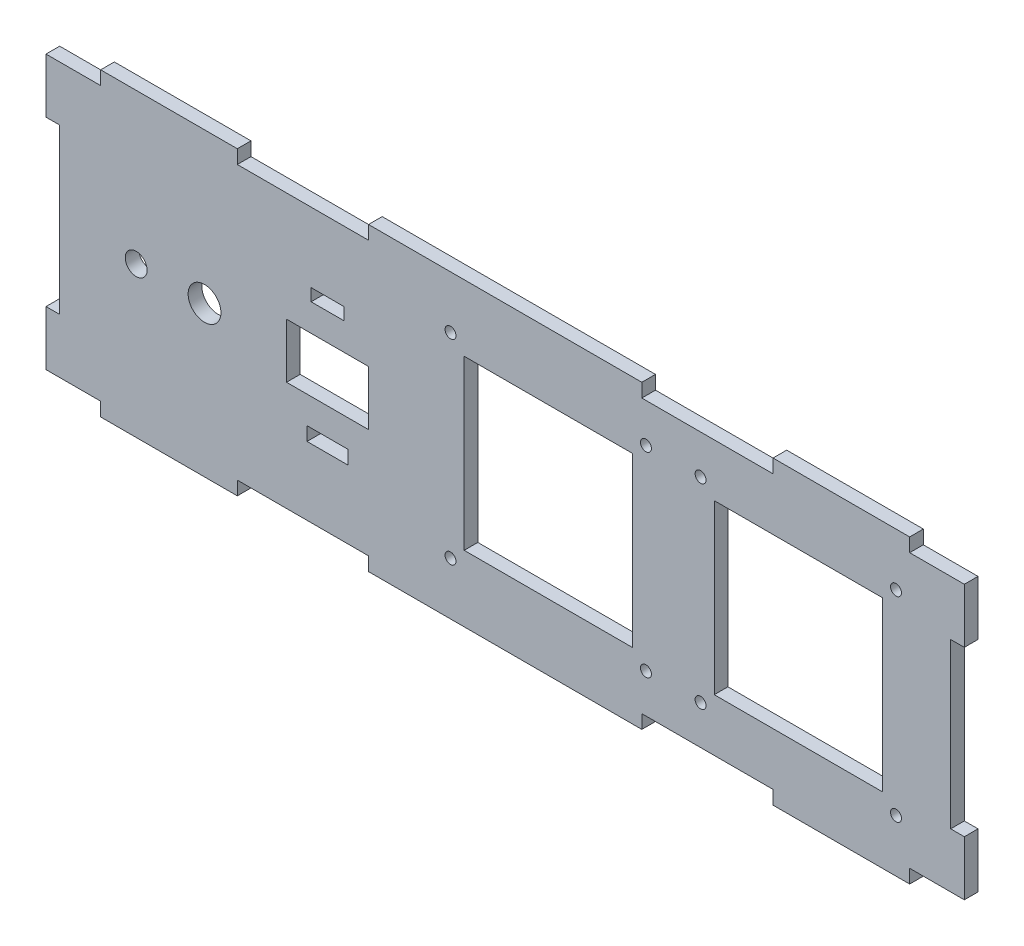
SolidWorks part; units mm, degrees
ref_plane "Front Plane" through (0, 0, 0) normal (0, 0, 1) x (1, 0, 0)
ref_plane "Top Plane" through (0, 0, 0) normal (0, 1, 0) x (1, 0, 0)
ref_plane "Right Plane" through (0, 0, 0) normal (1, 0, 0) x (0, 0, -1)
sketch "Sketch1" plane through (0, 0, 0) normal (0, 0, 1) x (1, 0, 0)
  line L0 (-168, 0) -> (168, 0) construction
  line L1 (168, -50) -> (-168, -50)
  line L2 (168, -50) -> (168, 50)
  line L3 (168, 50) -> (-168, 50)
  line L4 (-168, -50) -> (-168, 50)
  line L5 (168, -50) -> (-168, 50) construction
  line L6 (168, 50) -> (-168, -50) construction
  line L7 (0, 50) -> (0, -50) construction
  line L8 (-168, 30) -> (-163, 30)
  line L9 (-148, 50) -> (-98, 50)
  line L10 (-148, 50) -> (-148, 55)
  line L11 (-148, 55) -> (-98, 55)
  line L12 (-98, 50) -> (-98, 55)
  line L13 (0, 50) -> (-50, 50)
  line L15 (50, 55) -> (-50, 55)
  line L16 (-50, 50) -> (-50, 55)
  line L17 (-163, 30) -> (-163, -30)
  line L18 (-50, -50) -> (-50, -55)
  line L19 (50, -55) -> (-50, -55)
  line L20 (-168, -30) -> (-163, -30)
  line L21 (-148, -50) -> (-148, -55)
  line L22 (-98, -50) -> (-98, -55)
  line L23 (-148, -55) -> (-98, -55)
  line L24 (50, 50) -> (50, 55)
  line L25 (148, 50) -> (148, 55)
  line L26 (98, 50) -> (98, 55)
  line L27 (148, 55) -> (98, 55)
  line L28 (50, -50) -> (50, -55)
  line L29 (98, -50) -> (98, -55)
  line L30 (148, -50) -> (148, -55)
  line L31 (148, -55) -> (98, -55)
  line L32 (168, -30) -> (163, -30)
  line L33 (168, 30) -> (163, 30)
  line L34 (163, 30) -> (163, -30)
  line L35 (-50, 50) -> (50, 50)
  line L36 (-148, 50) -> (-98, 50)
  line L37 (98, 50) -> (148, 50)
  line L38 (168, 30) -> (168, -30)
  line L39 (148, -50) -> (98, -50)
  line L40 (50, -50) -> (-50, -50)
  line L41 (-98, -50) -> (-148, -50)
  line L42 (-168, 30) -> (-168, -30)
  line L54 (-20, 35.75) -> (51.5, -35.75) construction
  line L55 (-20, -35.75) -> (51.5, 35.75) construction
  line L56 (71.5, 35.75) -> (143, -35.75) construction
  line L57 (71.5, -35.75) -> (143, 35.75) construction
  line L58 (-65, 10) -> (-65, 35.75) construction
  line L59 (46.5, -30.75) -> (-15, -30.75)
  line L60 (46.5, -30.75) -> (46.5, 30.75)
  line L61 (46.5, 30.75) -> (-15, 30.75)
  line L62 (-15, -30.75) -> (-15, 30.75)
  line L63 (46.5, -30.75) -> (-15, 30.75) construction
  line L64 (46.5, 30.75) -> (-15, -30.75) construction
  line L65 (138, -30.75) -> (76.5, -30.75)
  line L66 (138, -30.75) -> (138, 30.75)
  line L67 (138, 30.75) -> (76.5, 30.75)
  line L68 (76.5, -30.75) -> (76.5, 30.75)
  line L69 (138, -30.75) -> (76.5, 30.75) construction
  line L70 (138, 30.75) -> (76.5, -30.75) construction
  line L71 (-80, -10) -> (-50, -10)
  line L72 (-80, -10) -> (-80, 10)
  line L73 (-80, 10) -> (-50, 10)
  line L74 (-50, -10) -> (-50, 10)
  line L75 (-80, -10) -> (-50, 10) construction
  line L76 (-80, 10) -> (-50, -10) construction
  line L77 (-71, 24.5) -> (-59, 24.5)
  line L81 (-71, 20) -> (-71, 24.5)
  line L82 (-71, 20) -> (-59, 20)
  line L83 (-65, 10) -> (-65, -50) construction
  line L84 (-65, 35.75) -> (-65, 50) construction
  line L85 (-57.5, -20) -> (-72.5, -20)
  line L86 (-72.5, -20) -> (-72.5, -25)
  line L87 (-72.5, -25) -> (-57.5, -25)
  line L88 (-57.5, -20) -> (-57.5, -25)
  line L89 (-59, 20) -> (-59, 24.5)
  circle A0 centre (-20, 35.75) radius 2
  circle A1 centre (51.5, 35.75) radius 2
  circle A2 centre (-20, -35.75) radius 2
  circle A3 centre (51.5, -35.75) radius 2
  circle A4 centre (71.5, 35.75) radius 2
  circle A5 centre (143, 35.75) radius 2
  circle A6 centre (71.5, -35.75) radius 2
  circle A7 centre (143, -35.75) radius 2
  circle A8 centre (-135, 0) radius 4
  circle A9 centre (-110, 0) radius 6
  point P0 (0, 0)
  point P24 (-163, 0)
  point P31 (0, 55)
  point P37 (0, -55)
  point P61 (15.75, 0)
  point P66 (107.25, 0)
  point P75 (-65, 0)
  point P86 (-65, 24.5)
  point P93 (-65, -25)
  point P94 (-65, -20)
  point P96 (-65, 20)
  dimension "D17" = 61.5
  dimension "D11" = 12
  dimension "D14" = 28
  dimension "D18" = 53
  dimension "D1" = 100
  dimension "D2" = 336
  dimension "D3" = 5
  dimension "D4" = 5
  dimension "D5" = 50
  dimension "D6" = 50
  dimension "D7" = 5
  dimension "D8" = 30
  dimension "D9" = 20
  dimension "D10" = 20
  dimension "D12" = 71.5
  dimension "D13" = 71.5
  dimension "D15" = 71.5
  dimension "D16" = 71.5
  dimension "D19" = 30
  dimension "D20" = 20
  dimension "D21" = 30
  dimension "D22" = 4.5
  dimension "D23" = 6
  dimension "D24" = 10
  dimension "D25" = 7.5
  dimension "D26" = 5
  dimension "D27" = 10
extrude "Boss-Extrude1" add sketch "Sketch1" along normal blind 5 contours L34 L33 L2 L3 L4 L8 L17 L20 L1 L32 | L28 L1 L18 L19 | L31 L30 L1 L29 | L25 L27 L26 L3 | L3 L12 L11 L10 | L23 L22 L41 L21 | L35 L24 L15 L16
